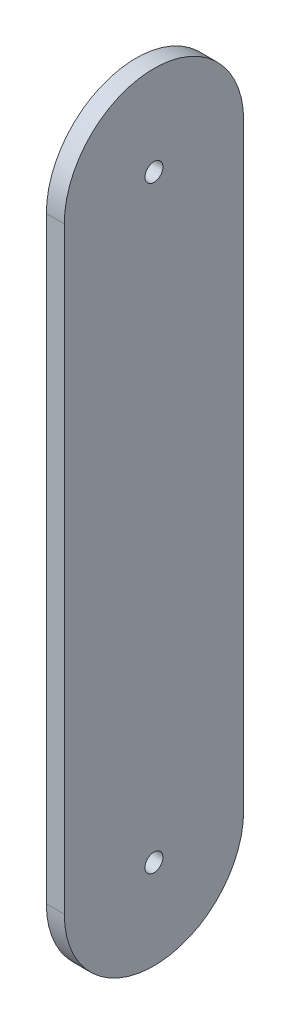
SolidWorks part; units mm, degrees
ref_plane "Front Plane" through (0, 0, 0) normal (0, 0, 1) x (1, 0, 0)
ref_plane "Top Plane" through (0, 0, 0) normal (0, 1, 0) x (1, 0, 0)
ref_plane "Right Plane" through (0, 0, 0) normal (1, 0, 0) x (0, 0, -1)
sketch "Sketch1" plane through (0, 0, 0) normal (1, 0, 0) x (0, 0, -1)
  line L0 (-5.4052, 0) -> (8.0572, 0) construction
  line L2 (0.1698, 50) -> (0.1698, -50)
  line L4 (-29.8302, 50) -> (-29.8302, -50)
  line L5 (0.168, 50.233) -> (-0.178, -53.2114) construction
  line L6 (0.1697, -49.9382) -> (-0.1809, 53.2245) construction
  arc A0 (0.1698, 50) -> (-29.8302, 50) centre (-14.8302, 50) ccw
  arc A1 (0.1698, -50) -> (-29.8302, -50) centre (-14.8302, -50) cw
  circle A2 centre (-14.8302, -50) radius 1.5
  point P0 (0, 0)
  dimension "D3" = 3
  dimension "D1" = 100
  dimension "D2" = 30
extrude "Boss-Extrude1" add sketch "Sketch1" along normal blind 3
sketch "Sketch2" plane through (3, 0, 0) normal (1, 0, 0) x (0, 0, -1)
  circle A0 centre (-14.8302, 50) radius 1.5
  dimension "D1" = 3
  dimension "D2" = 15
extrude "Cut-Extrude1" cut sketch "Sketch2" against normal blind 10
